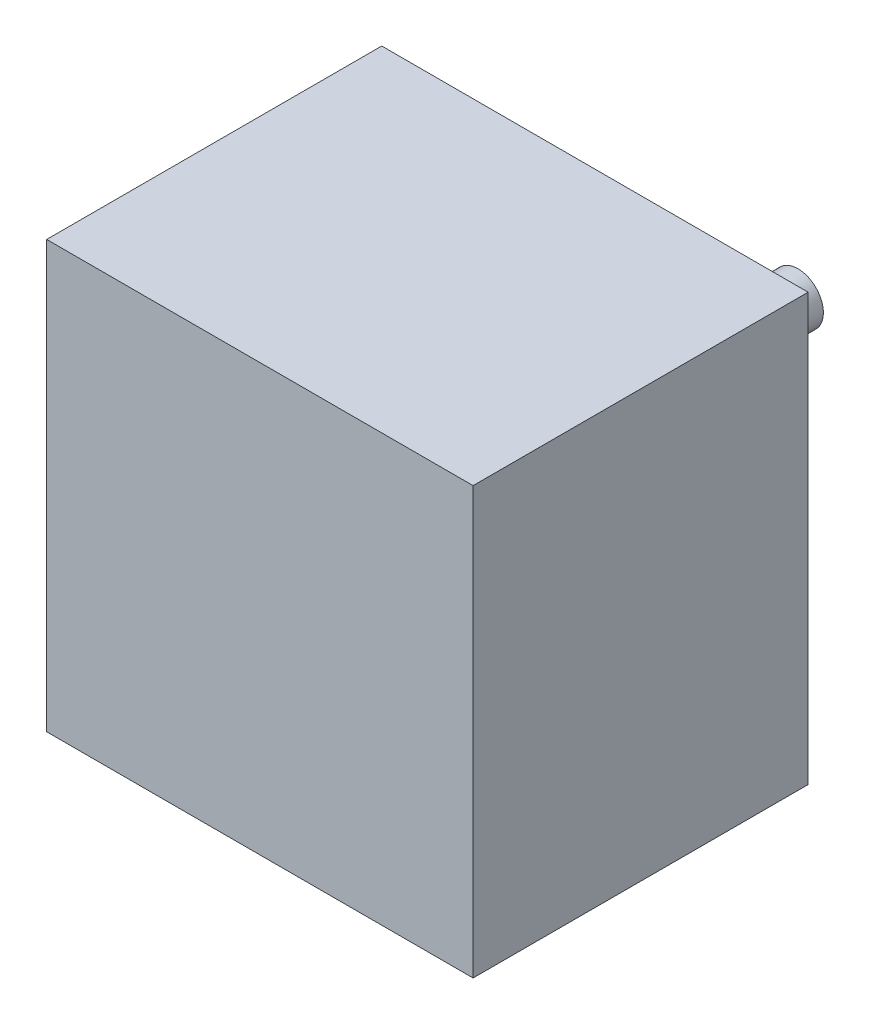
SolidWorks part; units mm, degrees
ref_plane "前视基准面" through (0, 0, 0) normal (0, 0, 1) x (1, 0, 0)
ref_plane "上视基准面" through (0, 0, 0) normal (0, 1, 0) x (1, 0, 0)
ref_plane "右视基准面" through (0, 0, 0) normal (1, 0, 0) x (0, 0, -1)
sketch "草图1" plane through (0, 0, 0) normal (0, 0, 1) x (1, 0, 0)
  line L1 (0, 0) -> (-42, 0)
  line L2 (0, 0) -> (0, 42)
  line L3 (0, 42) -> (-42, 42)
  line L4 (-42, 0) -> (-42, 42)
  dimension "D1" = 42
  dimension "D2" = 42
extrude "凸台-拉伸1" add sketch "草图1" along normal blind 33
sketch "草图3" plane through (0, 0, 0) normal (0, 0, -1) x (-1, 0, 0)
  line L0 (0, 42) -> (42, 42) construction
  line L1 (0, 0) -> (0, 42) construction
  circle A0 centre (21, 21) radius 11
  dimension "D3" = 22
  dimension "D1" = 21
  dimension "D2" = 21
extrude "凸台-拉伸2" add sketch "草图3" along normal blind 2
sketch "草图4" plane through (0, 0, -2) normal (0, 0, -1) x (-1, 0, 0)
  circle A0 centre (21, 21) radius 2.5
  dimension "D1" = 5
extrude "凸台-拉伸3" add sketch "草图4" along normal blind 18
sketch "草图5" plane through (0, 0, 0) normal (0, 0, -1) x (-1, 0, 0)
  line L0 (0, 0) -> (5.5, 0) construction
  line L1 (42, 0) -> (0, 0) construction
  line L2 (5.5, 0) -> (5.5, 5.5) construction
  line L3 (5.5, 5.5) -> (36.5, 5.5) construction
  line L4 (36.5, 5.5) -> (36.5, 36.5) construction
  line L5 (36.5, 36.5) -> (5.5, 36.5) construction
  circle A0 centre (5.5, 5.5) radius 1.5
  circle A1 centre (36.5, 5.5) radius 1.5
  circle A2 centre (36.5, 36.5) radius 1.5
  circle A3 centre (5.5, 36.5) radius 1.5
  dimension "D6" = 3
  dimension "D7" = 3
  dimension "D8" = 3
  dimension "D9" = 3
  dimension "D1" = 5.5
  dimension "D2" = 5.5
  dimension "D3" = 31
  dimension "D4" = 31
  dimension "D5" = 31
extrude "切除-拉伸1" cut sketch "草图5" against normal blind 8
